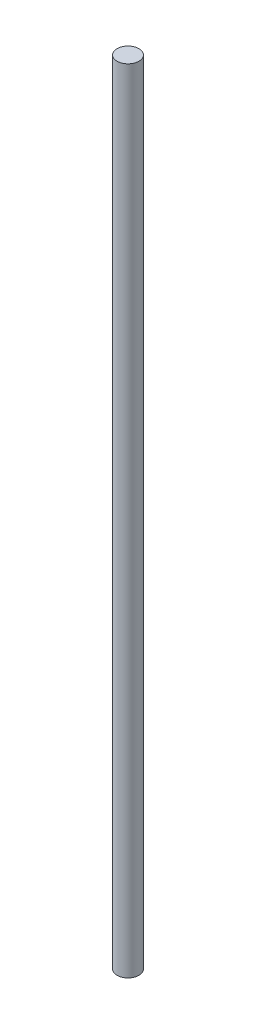
SolidWorks part; units mm, degrees
ref_plane "前视基准面" through (0, 0, 0) normal (0, 0, 1) x (1, 0, 0)
ref_plane "上视基准面" through (0, 0, 0) normal (0, 1, 0) x (1, 0, 0)
ref_plane "右视基准面" through (0, 0, 0) normal (1, 0, 0) x (0, 0, -1)
other "Configuration Table"
sketch "草图1" plane through (0, 0, 0) normal (0, 1, 0) x (1, 0, 0)
  circle A0 centre (0, 0) radius 2
extrude "凸台-拉伸1" add sketch "草图1" along normal blind 145
